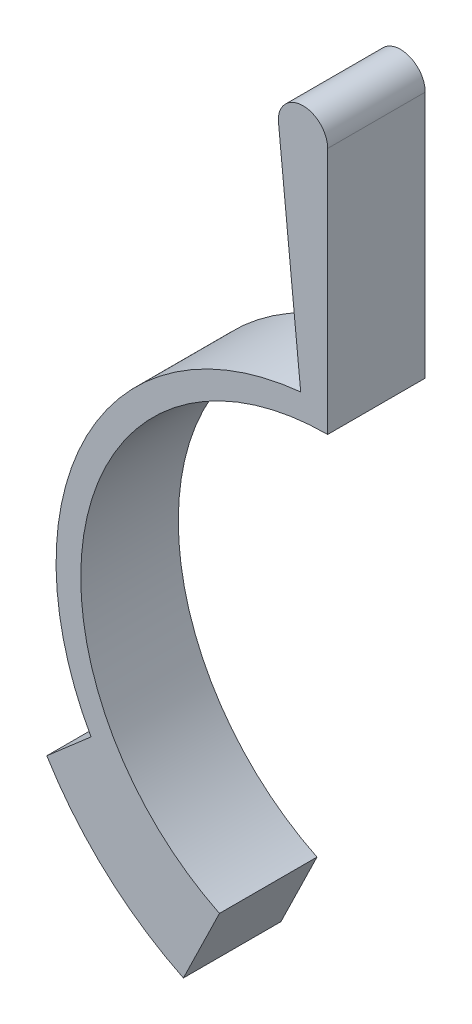
SolidWorks part; units mm, degrees
ref_plane "Plano frontal" through (0, 0, 0) normal (0, 0, 1) x (1, 0, 0)
ref_plane "Plano superior" through (0, 0, 0) normal (0, 1, 0) x (1, 0, 0)
ref_plane "Plano direito" through (0, 0, 0) normal (1, 0, 0) x (0, 0, -1)
sketch "Esboço1" plane through (0, 0, 0) normal (0, 0, 1) x (1, 0, 0)
  line L0 (2.4622, -10.7382) -> (2.4622, -0.6722)
  line L1 (-31.6634, -61.6056) -> (-26.2912, -56.9322)
  line L2 (-18.9512, -45.6683) -> (2.4622, -40.7382) construction
  line L3 (2.4622, -0.6722) -> (2.4622, 19.3608)
  line L4 (-0.8161, -7.9015) -> (-3.5378, 19.3608)
  line L6 (-15.0684, -76.6921) -> (-10.6857, -67.7036)
  arc A1 (2.4622, -10.7382) -> (-10.6857, -67.7036) centre (2.4622, -40.7382) ccw
  arc A2 (-0.8161, -7.9015) -> (-26.2912, -56.9322) centre (2.4622, -40.7382) ccw
  arc A3 (2.4622, 19.3608) -> (-3.4786, 18.7677) centre (-0.5378, 19.3608) ccw
  arc A5 (-31.6634, -61.6056) -> (-15.0684, -76.6921) centre (2.4622, -40.7382) ccw
  dimension "D1" = 6
  dimension "D2" = 30
  dimension "D3" = 33
  dimension "D4" = 40
extrude "Ressalto-extrusão1" add sketch "Esboço1" along normal up to vertex (106.1727 mm away)
ref_plane "Plano1" through (18.0373, -8.7947, 0) normal (0.8988, -0.4383, 0) x (0, 0, -1)
sketch "Esboço2" plane through (18.0373, -8.7947, 0) normal (0.8988, -0.4383, 0) x (0, 0, -1)
  line L0 (-11.85, -75.5383) -> (0, -75.5383)
  dimension "D1" = 11.85
  dimension "D2" = 11.85
